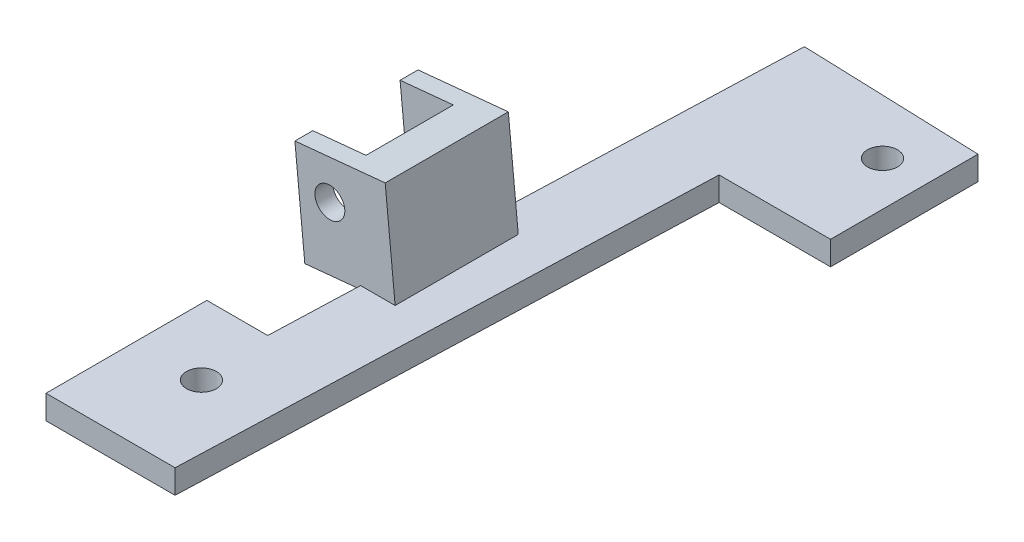
SolidWorks part; units mm, degrees
ref_plane "Front Plane" through (0, 0, 0) normal (0, 0, 1) x (1, 0, 0)
ref_plane "Top Plane" through (0, 0, 0) normal (0, 1, 0) x (1, 0, 0)
ref_plane "Right Plane" through (0, 0, 0) normal (1, 0, 0) x (0, 0, -1)
sketch "Sketch1" plane through (0, 0, 0) normal (0, 0, 1) x (1, 0, 0)
  line L0 (476.9237, 158.5913) -> (479.0335, 137.0791)
  line L1 (479.0335, 137.0791) -> (498.2247, 138.9613)
  line L2 (498.2247, 138.9613) -> (496.115, 160.4735)
  line L3 (496.115, 160.4735) -> (476.9237, 158.5913)
  line L4 (485.2846, 141.5205) -> (469.8952, 140.0112) construction
  line L5 (485.2846, 141.5205) -> (469.8952, 140.0112)
  arc A0 (489.9044, 158.7414) -> (483.4252, 160.4795) centre (484.3549, 151) ccw construction
  arc A1 (491.3026, 144.4842) -> (489.9044, 158.7414) centre (484.3549, 151) ccw construction
  arc A2 (485.2846, 141.5205) -> (491.3026, 144.4842) centre (484.3549, 151) ccw construction
  arc A3 (489.9044, 158.7414) -> (483.4252, 160.4795) centre (484.3549, 151) ccw
  arc A4 (491.3026, 144.4842) -> (489.9044, 158.7414) centre (484.3549, 151) ccw
  arc A5 (485.2846, 141.5205) -> (491.3026, 144.4842) centre (484.3549, 151) ccw
  dimension "D1" = 6.35
  dimension "D2" = 3.81
extrude "Boss-Extrude5" add sketch "Sketch1" against normal blind 22.352 contours A5 L5 L0 L1 L2 L3 A3 A4
sketch "Sketch2" plane through (0, 0, -22.352) normal (0, 0, -1) x (-1, 0, 0)
  line L0 (-488.2317, 159.7003) -> (-476.9237, 158.5913)
  line L1 (-476.9237, 158.5913) -> (-478.6616, 140.8709)
  line L2 (-478.6616, 140.8709) -> (-485.2846, 141.5205)
  arc A0 (-485.2846, 141.5205) -> (-488.2317, 159.7003) centre (-484.3549, 151) cw
  circle A1 centre (-484.3549, 151) radius 3.175 construction
  circle A2 centre (-484.3549, 151) radius 3.175
  circle A3 centre (-484.3549, 151) radius 3.175
  arc M5 (-485.2846, 141.5205) -> (-488.2317, 159.7003) centre (-484.3549, 151) cw
  line M10 (-478.6616, 140.8709) -> (-485.2846, 141.5205)
extrude "Boss-Extrude7" add sketch "Sketch2" against normal blind 3.81 contours L1 L0 A2 M5 M10
sketch "Sketch3" plane through (0, 0, 0) normal (0, 0, 1) x (1, 0, 0)
  line L0 (476.9237, 158.5913) -> (479.0335, 137.0791)
  line L1 (479.0335, 137.0791) -> (498.2247, 138.9613)
  line L2 (498.2247, 138.9613) -> (496.115, 160.4735)
  line L3 (496.115, 160.4735) -> (476.9237, 158.5913)
  circle A0 centre (484.3549, 151) radius 3.175 construction
  circle A1 centre (484.3549, 151) radius 3.175
  circle A2 centre (484.3549, 151) radius 3.175
  arc M6 (488.2317, 159.7003) -> (485.2846, 141.5205) centre (484.3549, 151) cw
  line M7 (485.2846, 141.5205) -> (478.6616, 140.8709)
  line M8 (478.6616, 140.8709) -> (479.0335, 137.0791)
  line M9 (479.0335, 137.0791) -> (498.2247, 138.9613)
  line M10 (498.2247, 138.9613) -> (496.115, 160.4735)
  line M11 (496.115, 160.4735) -> (488.2317, 159.7003)
extrude "Boss-Extrude8" add sketch "Sketch3" along normal blind 3.81 contours L3 L0 A1 M6 M7 | M11 M6 M7 M8 M9 M10
ref_plane "Plane1" through (0, 138.9613, 0) normal (0, 1, 0) x (1, 0, 0)
sketch "Sketch4" plane through (0, 138.9613, 0) normal (0, 1, 0) x (1, 0, 0)
  line L0 (494.0725, 87.3113) -> (532.2914, 85.9701)
  line L2 (494.0725, 87.3113) -> (490.2062, -22.86)
  line L4 (508.6117, 54.6403) -> (504.6925, -57.0385)
  line L5 (532.2914, 85.9701) -> (532.2914, 54.6403)
  line L6 (532.2914, 54.6403) -> (508.6117, 54.6403)
  line L7 (504.6925, -57.0385) -> (477.2694, -57.0385)
  line L8 (477.2694, -57.0385) -> (477.2694, -22.86)
  line L9 (477.2694, -22.86) -> (490.2062, -22.86)
  dimension "D1" = 90
  dimension "D2" = 111.7476
  dimension "D3" = 180
  dimension "D4" = 110.1713
extrude "Boss-Extrude9" add sketch "Sketch4" against normal blind 5.08
sketch "Sketch6" plane through (0, 138.9613, 0) normal (0, 1, 0) x (1, 0, 0)
  circle A0 centre (491.3661, -38.1051) radius 3.175
  circle A1 centre (522.9171, 75.0492) radius 3.175
  point P4 (522.9171, 75.0492)
  point P5 (491.3661, -38.1051)
  dimension "D1" = 6.35
  dimension "D2" = 6.35
extrude "Cut-Extrude1" cut sketch "Sketch6" against normal blind 6.35
